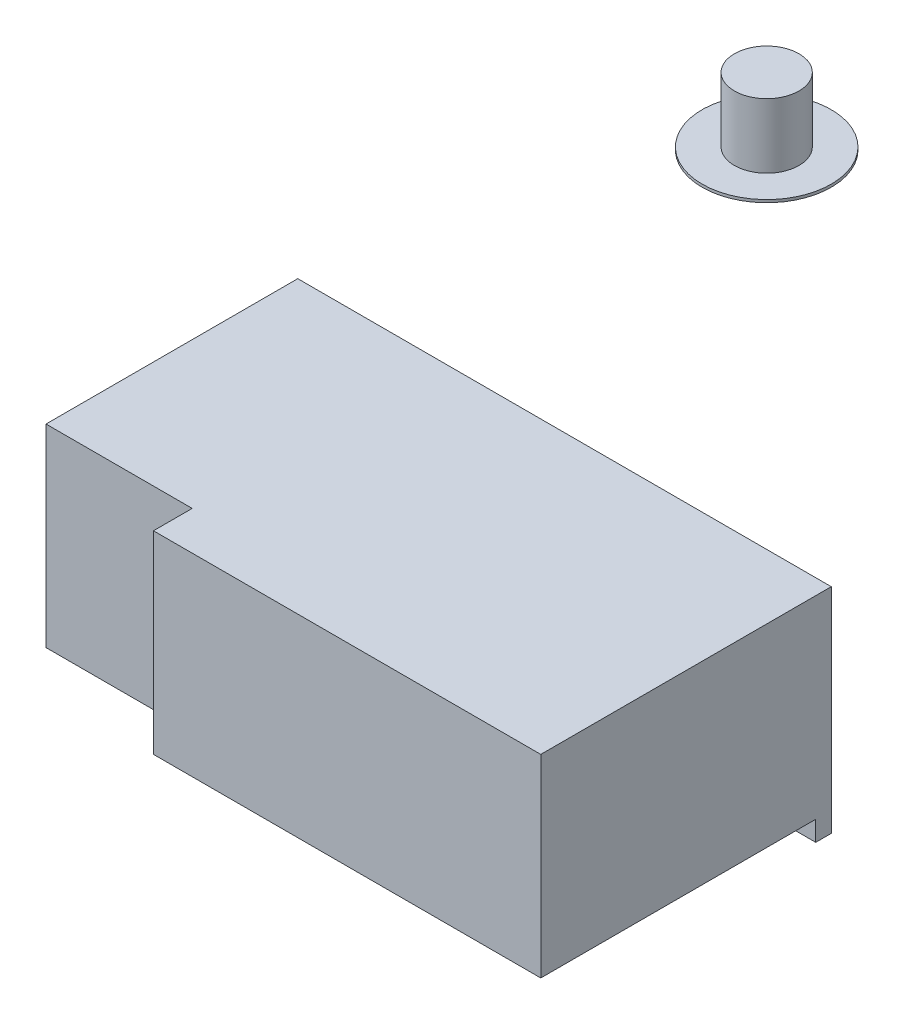
SolidWorks part; units mm, degrees
ref_plane "Alzado" through (0, 0, 0) normal (0, 0, 1) x (1, 0, 0)
ref_plane "Planta" through (0, 0, 0) normal (0, 1, 0) x (1, 0, 0)
ref_plane "Vista lateral" through (0, 0, 0) normal (1, 0, 0) x (0, 0, -1)
sketch "Croquis1" plane through (0, 0, 0) normal (0, 1, 0) x (1, 0, 0)
  line L1 (-15, 22.5) -> (15, 22.5)
  line L2 (-15, 22.5) -> (-15, -22.5)
  line L3 (-15, -22.5) -> (15, -22.5)
  line L4 (15, 22.5) -> (15, -22.5)
  line L5 (-15, 22.5) -> (15, -22.5) construction
  line L6 (-15, -22.5) -> (15, 22.5) construction
  point P0 (0, 0)
  dimension "D1" = 30
  dimension "D2" = 45
extrude "Saliente-Extruir1" add sketch "Croquis1" along normal mid plane 15
sketch "Croquis2" plane through (0, 7.5, 0) normal (0, 1, 0) x (1, 0, 0)
  line L0 (15, -22.5) -> (15, 22.5) construction
  line L1 (-10, 17.5) -> (10, 17.5)
  line L2 (-10, 17.5) -> (-10, 2.5)
  line L3 (-10, 2.5) -> (10, 2.5)
  line L4 (10, 17.5) -> (10, 2.5)
  line L5 (15, 22.5) -> (-15, 22.5) construction
  line L6 (-15, 22.5) -> (-15, -22.5) construction
  dimension "D1" = 5
  dimension "D2" = 15
  dimension "D3" = 5
  dimension "D4" = 5
extrude "Saliente-Extruir2" add sketch "Croquis2" along normal blind 15
sketch "Croquis3" plane through (0, -7.5, 0) normal (0, -1, 0) x (1, 0, 0)
  line L0 (15, 22.5) -> (15, -22.5) construction
  line L1 (-10, -2.5) -> (10, -2.5)
  line L2 (-10, -2.5) -> (-10, -17.5)
  line L3 (-10, -17.5) -> (10, -17.5)
  line L4 (10, -2.5) -> (10, -17.5)
  line L5 (-15, -22.5) -> (-15, 22.5) construction
  line L6 (15, -22.5) -> (-15, -22.5) construction
  dimension "D1" = 15
  dimension "D2" = 5
  dimension "D3" = 5
  dimension "D4" = 5
extrude "Saliente-Extruir3" add sketch "Croquis3" along normal blind 8
sketch "Croquis4" plane through (0, 22.5, 0) normal (0, 1, 0) x (1, 0, 0)
  line L0 (10, 17.5) -> (-10, 17.5) construction
  line L1 (10, 2.5) -> (10, 17.5) construction
  circle A0 centre (0, 10) radius 5
  point P5 (0, 17.5)
  point P8 (10, 10)
  dimension "D1" = 10
extrude "Saliente-Extruir4" add sketch "Croquis4" along normal blind 2
sketch "Croquis5" plane through (0, 24.5, 0) normal (0, 1, 0) x (1, 0, 0)
  circle A0 centre (0, 10) radius 2.5
  dimension "D1" = 5
extrude "Saliente-Extruir5" add sketch "Croquis5" along normal blind 5
sketch "Croquis6" plane through (-15, 0, 0) normal (-1, 0, 0) x (0, 0, 1)
  line L0 (-22.5, 7.5) -> (22.5, 7.5) construction
  line L1 (0, 7.5) -> (19.5, 7.5)
  line L2 (0, 7.5) -> (0, -7.5)
  line L3 (0, -7.5) -> (19.5, -7.5)
  line L4 (19.5, 7.5) -> (19.5, -7.5)
  line L5 (-22.5, -7.5) -> (22.5, -7.5) construction
  line L6 (22.5, 7.5) -> (22.5, -7.5) construction
  dimension "D1" = 3
extrude "Saliente-Extruir6" add sketch "Croquis6" along normal blind 16
sketch "Croquis7" plane through (0, -7.5, 0) normal (0, -1, 0) x (1, 0, 0)
  line L0 (15, 22.5) -> (15, -22.5) construction
  line L1 (-31, 0) -> (15, 0)
  line L2 (-31, 0) -> (-31, 1.2032)
  line L3 (-31, 1.2032) -> (15, 1.2032)
  line L4 (15, 0) -> (15, 1.2032)
extrude "Saliente-Extruir7" add sketch "Croquis7" along normal blind 1.55
sketch "Croquis9" plane through (-15, 0, 0) normal (-1, 0, 0) x (0, 0, 1)
  line L0 (0, 7.5) -> (0, -7.5) construction
  line L1 (0, 24.2879) -> (-23.5959, 24.2879)
  line L2 (0, 24.2879) -> (0, -21.6569)
  line L3 (0, -21.6569) -> (-23.5959, -21.6569)
  line L4 (-23.5959, 24.2879) -> (-23.5959, -21.6569)
extrude "Cortar-Extruir1" cut sketch "Croquis9" against normal blind 41.55
sketch "Croquis10" plane through (0, 7.5, 0) normal (0, 1, 0) x (1, 0, 0)
  line L0 (-31, 0) -> (15, 0) construction
  line L1 (-31, -19.5) -> (-26.3221, -19.5)
  line L2 (-31, -19.5) -> (-31, 0)
  line L3 (-31, 0) -> (-26.3221, 0)
  line L4 (-26.3221, -19.5) -> (-26.3221, 0)
extrude "Cortar-Extruir2" cut sketch "Croquis10" against normal blind 20
